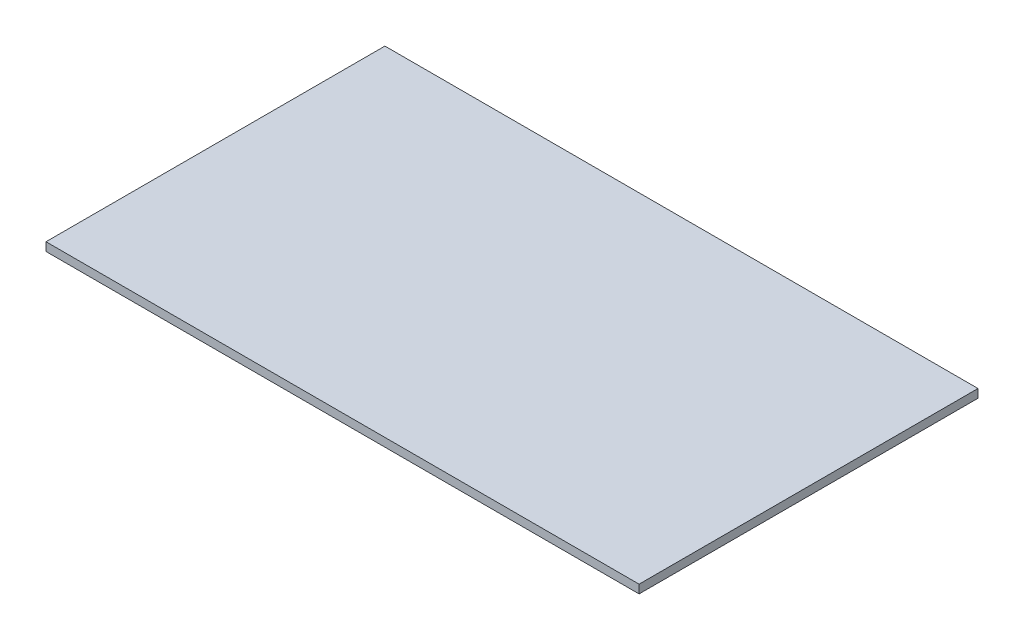
SolidWorks part; units mm, degrees
ref_plane "Plan de face" through (0, 0, 0) normal (0, 0, 1) x (1, 0, 0)
ref_plane "Plan de dessus" through (0, 0, 0) normal (0, 1, 0) x (1, 0, 0)
ref_plane "Plan de droite" through (0, 0, 0) normal (1, 0, 0) x (0, 0, -1)
sketch "Esquisse1" plane through (0, 0, 0) normal (0, 1, 0) x (1, 0, 0)
  line L0 (-137.5, 0) -> (137.5, 0) construction
  line L1 (-175, 100) -> (175, 100)
  line L2 (-175, 100) -> (-175, -100)
  line L3 (-175, -100) -> (175, -100)
  line L4 (175, 100) -> (175, -100)
  line L5 (0, -82.5) -> (0, 82.5) construction
  dimension "D1" = 350
  dimension "D2" = 200
  dimension "D3" = 100
  dimension "D4" = 175
extrude "Boss.-Extru.1" add sketch "Esquisse1" along normal blind 5
